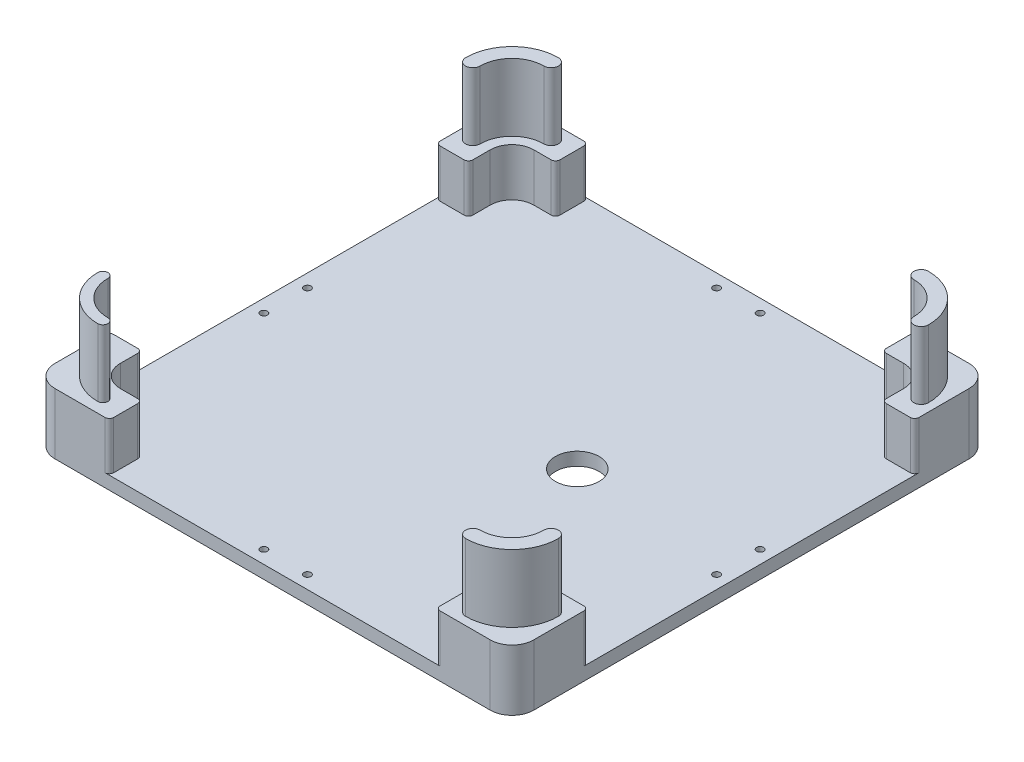
SolidWorks part; units mm, degrees
other "Markup1"
sketch "Sketch10" plane through (110, 59, 110) normal (0.036, 0.9985, 0.0406) x (0.9978, -0.0382, 0.0539)
ref_plane "Front Plane" through (0, 0, 0) normal (0, 0, 1) x (1, 0, 0)
ref_plane "Top Plane" through (0, 0, 0) normal (0, 1, 0) x (1, 0, 0)
ref_plane "Right Plane" through (0, 0, 0) normal (1, 0, 0) x (0, 0, -1)
sketch "Sketch2" plane through (0, 0, 0) normal (0, 1, 0) x (1, 0, 0)
  line L1 (-110, -110) -> (110, -110)
  line L2 (-110, -110) -> (-110, 110)
  line L3 (-110, 110) -> (110, 110)
  line L4 (110, -110) -> (110, 110)
  line L5 (0, 110) -> (0, -110) construction
  line L6 (-110, 0) -> (110, 0) construction
  point P0 (0, 0)
  dimension "D1" = 220
  dimension "D2" = 220
extrude "Boss-Extrude1" add sketch "Sketch2" along normal blind 6
fillet "Fillet1" radius 10 4 edges at (-110, 3, -110) (-110, 3, 110) (110, 3, -110) (110, 3, 110)
sketch "Sketch3" plane through (0, 6, 0) normal (0, 1, 0) x (1, 0, 0)
  line L0 (75, 95) -> (75, 110)
  line L1 (75, 95) -> (85, 95)
  line L2 (95, 85) -> (95, 75)
  line L3 (95, 75) -> (110, 75)
  line L4 (110, 100) -> (110, 75)
  line L5 (75, 110) -> (100, 110)
  line L6 (110, -100) -> (110, 100) construction
  line L7 (100, 110) -> (-100, 110) construction
  line L8 (0, -32.45) -> (0, 32.45) construction
  line L9 (-75, 110) -> (-100, 110)
  line L10 (-110, 100) -> (-110, 75)
  line L11 (-95, 75) -> (-110, 75)
  line L12 (-95, 85) -> (-95, 75)
  line L13 (-75, 95) -> (-85, 95)
  line L14 (-75, 95) -> (-75, 110)
  line L15 (-32.45, 0) -> (32.45, 0) construction
  line L16 (-75, -95) -> (-75, -110)
  line L17 (-75, -95) -> (-85, -95)
  line L18 (-95, -85) -> (-95, -75)
  line L19 (-95, -75) -> (-110, -75)
  line L20 (-110, -100) -> (-110, -75)
  line L21 (-75, -110) -> (-100, -110)
  line L22 (75, -110) -> (100, -110)
  line L23 (110, -100) -> (110, -75)
  line L24 (95, -75) -> (110, -75)
  line L25 (95, -85) -> (95, -75)
  line L26 (75, -95) -> (85, -95)
  line L27 (75, -95) -> (75, -110)
  arc A0 (95, 85) -> (85, 95) centre (85, 85) ccw
  arc A1 (100, 110) -> (110, 100) centre (100, 100) cw
  arc A2 (110, 100) -> (100, 110) centre (100, 100) ccw construction
  arc A3 (-100, 110) -> (-110, 100) centre (-100, 100) ccw
  arc A4 (-95, 85) -> (-85, 95) centre (-85, 85) cw
  arc A5 (-95, -85) -> (-85, -95) centre (-85, -85) ccw
  arc A6 (-100, -110) -> (-110, -100) centre (-100, -100) cw
  arc A7 (100, -110) -> (110, -100) centre (100, -100) ccw
  arc A8 (95, -85) -> (85, -95) centre (85, -85) cw
  dimension "D3" = 10
  dimension "D4" = 35
  dimension "D1" = 15
  dimension "D2" = 15
  dimension "D5" = 35
  dimension "D6" = 10
  dimension "D7" = 10
sketch "Sketch4" plane through (0, 6, 0) normal (0, 1, 0) x (1, 0, 0)
  line L0 (0, 0) -> (110, 0) construction
  line L1 (110, -100) -> (110, 100) construction
  line L2 (0, -32.45) -> (0, 32.45) construction
  line L3 (-32.45, 0) -> (32.45, 0) construction
  line L4 (-75, -95) -> (-75, -110) construction
  line L5 (-95, -75) -> (-110, -75) construction
  arc A0 (-103, -85) -> (-85, -103) centre (-85, -85) ccw construction
  arc A1 (-106.325, -85) -> (-85, -106.325) centre (-85, -85) ccw construction
  arc A2 (-99.675, -85) -> (-85, -99.675) centre (-85, -85) ccw construction
  arc A3 (-99.675, -85) -> (-106.325, -85) centre (-103, -85) ccw construction
  arc A4 (-85, -106.325) -> (-85, -99.675) centre (-85, -103) ccw construction
  arc A5 (-105.325, -85) -> (-85, -105.325) centre (-85, -85) ccw
  arc A10 (103, -85) -> (85, -103) centre (85, -85) cw construction
  arc A15 (106.325, -85) -> (85, -106.325) centre (85, -85) cw
  arc A20 (99.675, -85) -> (85, -99.675) centre (85, -85) cw
  arc A21 (99.675, -85) -> (106.325, -85) centre (103, -85) cw
  arc A22 (85, -106.325) -> (85, -99.675) centre (85, -103) cw
  arc A23 (103, 85) -> (85, 103) centre (85, 85) ccw construction
  arc A24 (106.325, 85) -> (85, 106.325) centre (85, 85) ccw
  arc A25 (99.675, 85) -> (85, 99.675) centre (85, 85) ccw
  arc A26 (99.675, 85) -> (106.325, 85) centre (103, 85) ccw
  arc A27 (85, 106.325) -> (85, 99.675) centre (85, 103) ccw
  arc A28 (-103, 85) -> (-85, 103) centre (-85, 85) cw construction
  arc A29 (-106.325, 85) -> (-85, 106.325) centre (-85, 85) cw
  arc A30 (-99.675, 85) -> (-85, 99.675) centre (-85, 85) cw
  arc A31 (-99.675, 85) -> (-106.325, 85) centre (-103, 85) cw
  arc A32 (-85, 106.325) -> (-85, 99.675) centre (-85, 103) cw
  arc A33 (-110, -100) -> (-100, -110) centre (-100, -100) ccw construction
  arc A34 (-85, -105.325) -> (-85, -100.675) centre (-85, -103) ccw
  arc A35 (-100.675, -85) -> (-85, -100.675) centre (-85, -85) ccw
  arc A36 (-100.675, -85) -> (-105.325, -85) centre (-103, -85) ccw
  point P0 (0, 0)
  point P5 (-97.7279, -97.7279)
  point P22 (97.7279, -97.7279)
  point P32 (97.7279, 97.7279)
  point P40 (-97.7279, 97.7279)
  dimension "D3" = 18
  dimension "D4" = 10
  dimension "D5" = 10
  dimension "D6" = 15
  dimension "D7" = 1
  dimension "D1" = 6.65
  dimension "D2" = 90
extrude "Boss-Extrude3" add sketch "Sketch4" along normal blind 53
extrude "Boss-Extrude4" add sketch "Sketch3" along normal blind 22
fillet "Fillet2" radius 2 16 edges at (110, 17, -75) (95, 17, -75) (75, 17, -95) (75, 17, -110) (110, 17, 75) (95, 17, 75) (75, 17, 95) (75, 17, 110) (-110, 17, 75) (-75, 17, 110) (-75, 17, 95) (-95, 17, 75) (-110, 17, -75) (-95, 17, -75) (-75, 17, -110) (-75, 17, -95)
sketch "Sketch7" plane through (0, 0, 0) normal (0, -1, 0) x (1, 0, 0)
  circle A0 centre (30, 0) radius 10
  dimension "D1" = 20
  dimension "D2" = 30
extrude "Cut-Extrude2" cut sketch "Sketch7" against normal up to next
sketch "Sketch8" plane through (0, 0, 0) normal (0, -1, 0) x (1, 0, 0)
  line L2 (0, 51.6454) -> (0, -51.6454) construction
  line L3 (0, -51.6454) -> (0, 0) construction
  line L4 (0, 0) -> (-130.2305, 0) construction
  line L5 (-110, -100) -> (-110, 100) construction
  circle A8 centre (-104, 10) radius 1.6
  circle A9 centre (-104, -10) radius 1.6
  circle A16 centre (0, 0) radius 5 construction
  circle A17 centre (-10, 104) radius 1.6
  circle A18 centre (10, 104) radius 1.6
  circle A19 centre (104, 10) radius 1.6
  circle A20 centre (104, -10) radius 1.6
  circle A21 centre (10, -104) radius 1.6
  circle A22 centre (-10, -104) radius 1.6
  point P12 (0, 0)
  point P27 (1.25, -1.25)
  point P29 (0, 0)
  dimension "D1" = 3.2
  dimension "D2" = 20
  dimension "D3" = 6
  dimension "D4" = 10
  dimension "D5" = 3.2
  dimension "D6" = 4
extrude "Cut-Extrude3" cut sketch "Sketch8" against normal up to next
sketch "Sketch9" plane through (0, 0, 0) normal (0, -1, 0) x (1, 0, 0)
  circle A0 centre (0, 0) radius 10 construction
  dimension "D1" = 20
